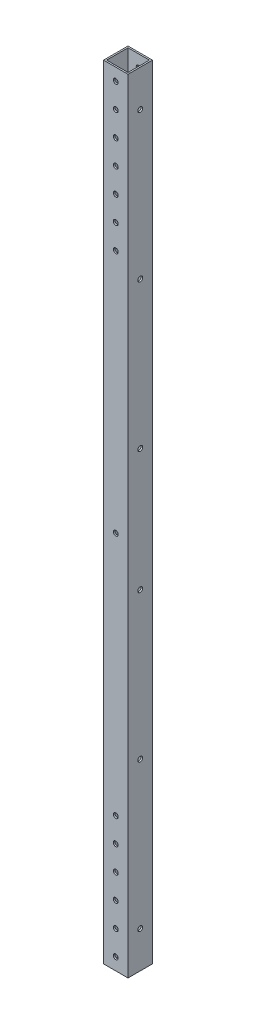
SolidWorks part; units mm, degrees
material "6061-T6 (SS)"
ref_plane "Front Plane" through (0, 0, 0) normal (0, 0, 1) x (1, 0, 0)
ref_plane "Top Plane" through (0, 0, 0) normal (0, 1, 0) x (1, 0, 0)
ref_plane "Right Plane" through (0, 0, 0) normal (1, 0, 0) x (0, 0, -1)
sketch "Sketch1" plane through (0, 0, 0) normal (0, 1, 0) x (1, 0, 0)
  line L1 (-12.7, -12.7) -> (12.7, -12.7)
  line L2 (-12.7, -12.7) -> (-12.7, 12.7)
  line L3 (-12.7, 12.7) -> (12.7, 12.7)
  line L4 (12.7, -12.7) -> (12.7, 12.7)
  line L5 (-12.7, -12.7) -> (12.7, 12.7) construction
  line L6 (-12.7, 12.7) -> (12.7, -12.7) construction
  line L7 (-11.1125, -11.1125) -> (11.1125, -11.1125)
  line L8 (-11.1125, -11.1125) -> (-11.1125, 11.1125)
  line L9 (-11.1125, 11.1125) -> (11.1125, 11.1125)
  line L10 (11.1125, -11.1125) -> (11.1125, 11.1125)
  line L11 (-11.1125, -11.1125) -> (11.1125, 11.1125) construction
  line L12 (-11.1125, 11.1125) -> (11.1125, -11.1125) construction
  point P0 (0, 0)
  point P6 (0, 0)
  dimension "D1" = 25.4
  dimension "D2" = 1.5875
extrude "Boss-Extrude1" add sketch "Sketch1" along normal blind 812.8
hole_wizard "#7 (0.201) Diameter Hole1" positions "Sketch2" profile "Sketch3" hole size "#7" standard "ANSI Inch"
sketch "Sketch2" plane through (0, 0, 12.7) normal (0, 0, 1) x (1, 0, 0)
  line L0 (-12.7, 0) -> (12.7, 0) construction
  point P0 (0, 12.7)
  point P12 (0, 38.1)
  point P13 (0, 63.5)
  point P14 (0, 88.9)
  point P15 (0, 114.3)
  point P16 (0, 139.7)
  point P26 (0, 393.7)
  point P36 (0, 647.7)
  point P37 (0, 673.1)
  point P38 (0, 698.5)
  point P39 (0, 723.9)
  point P40 (0, 749.3)
  point P41 (0, 774.7)
  point P42 (0, 800.1)
  point P43 (0, 165.1) [skipped]
  point P44 (0, 622.3) [skipped]
  point P45 (0, 368.3) [skipped]
  point P46 (0, 342.9) [skipped]
  point P47 (0, 317.5) [skipped]
  point P48 (0, 292.1) [skipped]
  point P49 (0, 266.7) [skipped]
  point P50 (0, 241.3) [skipped]
  point P51 (0, 215.9) [skipped]
  point P52 (0, 190.5) [skipped]
  point P53 (0, 596.9) [skipped]
  point P54 (0, 571.5) [skipped]
  point P55 (0, 546.1) [skipped]
  point P56 (0, 520.7) [skipped]
  point P57 (0, 495.3) [skipped]
  point P58 (0, 469.9) [skipped]
  point P59 (0, 444.5) [skipped]
  point P60 (0, 419.1) [skipped]
  dimension "D1" = 12.7
  dimension "D3" = 25.4
  dimension "D2" = 32
sketch "Sketch3" plane through (0, 12.7, 12.7) normal (1, 0, 0) x (0, -1, 0)
  line L0 (0, 0) -> (0, 25.4)
  line L1 (0, 25.4) -> (2.5527, 25.4)
  line L2 (2.5527, 25.4) -> (2.5527, 0)
  line L5 (2.5527, 0) -> (0, 0)
  line L11 (0, -6.35) -> (0, 107.95) construction
  dimension "Thru Hole Dia." = 5.1054
  dimension "Thru Hole Depth" = 25.4
hole_wizard "#7 (0.201) Diameter Hole2" positions "Sketch4" profile "Sketch5" hole size "#7" standard "ANSI Inch"
sketch "Sketch4" plane through (12.7, 0, 0) normal (1, 0, 0) x (0, 0, -1)
  line L0 (-12.7, 0) -> (12.7, 0) construction
  point P0 (0, 38.1)
  point P17 (0, 190.5)
  point P23 (0, 342.9)
  point P28 (0, 469.9)
  point P34 (0, 622.3)
  point P40 (0, 774.7)
  point P46 (0, 165.1) [skipped]
  point P47 (0, 139.7) [skipped]
  point P48 (0, 114.3) [skipped]
  point P49 (0, 88.9) [skipped]
  point P50 (0, 63.5) [skipped]
  point P52 (0, 317.5) [skipped]
  point P53 (0, 292.1) [skipped]
  point P54 (0, 266.7) [skipped]
  point P55 (0, 241.3) [skipped]
  point P56 (0, 215.9) [skipped]
  point P57 (0, 444.5) [skipped]
  point P58 (0, 419.1) [skipped]
  point P59 (0, 393.7) [skipped]
  point P60 (0, 368.3) [skipped]
  point P61 (0, 596.9) [skipped]
  point P62 (0, 571.5) [skipped]
  point P63 (0, 546.1) [skipped]
  point P64 (0, 520.7) [skipped]
  point P65 (0, 495.3) [skipped]
  point P66 (0, 749.3) [skipped]
  point P67 (0, 723.9) [skipped]
  point P68 (0, 698.5) [skipped]
  point P69 (0, 673.1) [skipped]
  point P70 (0, 647.7) [skipped]
  dimension "D1" = 38.1
  dimension "D3" = 152.4
  dimension "D2" = 30
sketch "Sketch5" plane through (12.7, 38.1, 0) normal (0, 1, 0) x (0, 0, -1)
  line L0 (0, 0) -> (0, 25.4)
  line L1 (0, 25.4) -> (2.5527, 25.4)
  line L2 (2.5527, 25.4) -> (2.5527, 0)
  line L5 (2.5527, 0) -> (0, 0)
  line L11 (0, -6.35) -> (0, 107.95) construction
  dimension "Thru Hole Dia." = 5.1054
  dimension "Thru Hole Depth" = 25.4
